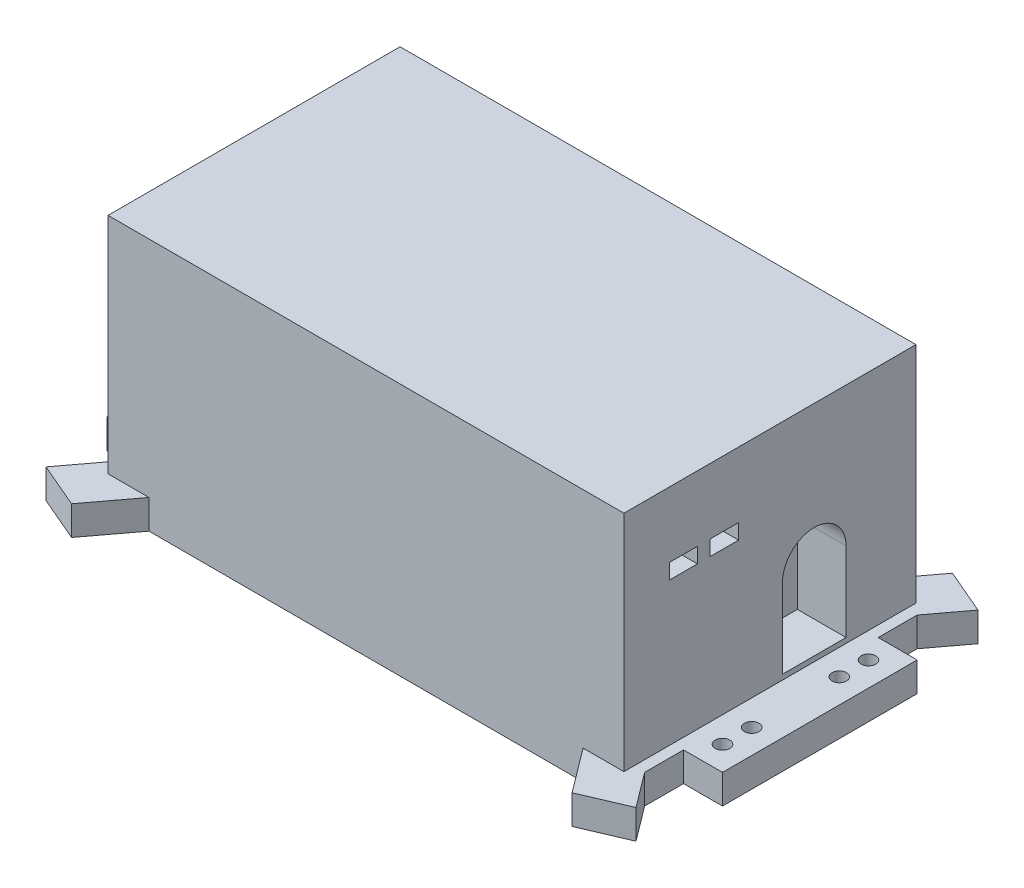
SolidWorks part; units mm, degrees
ref_plane "前视基准面" through (0, 0, 0) normal (0, 0, 1) x (1, 0, 0)
ref_plane "上视基准面" through (0, 0, 0) normal (0, 1, 0) x (1, 0, 0)
ref_plane "右视基准面" through (0, 0, 0) normal (1, 0, 0) x (0, 0, -1)
sketch "草图1" plane through (0, 0, 0) normal (0, 1, 0) x (1, 0, 0)
  line L0 (-65.7171, 0) -> (87.7991, 0) construction
  line L1 (44.6018, -30) -> (-44.6018, -30)
  line L3 (44.6018, 30) -> (-44.6018, 30)
  line L5 (53, -30) -> (-53, 30) construction
  line L6 (53, 30) -> (-53, -30) construction
  line L8 (63.25, -20) -> (63.25, 20)
  line L10 (-63.25, -20) -> (-63.25, 20)
  line L11 (63.25, 20) -> (55.25, 20)
  line L12 (55.25, 20) -> (55.25, 28)
  line L13 (55.25, 28) -> (60.6154, 35.1388)
  line L14 (60.6154, 35.1388) -> (51.4231, 39.0759)
  line L15 (51.4231, 39.0759) -> (44.6018, 30)
  line L16 (63.25, -20) -> (55.25, -20)
  line L17 (55.25, -20) -> (55.25, -28)
  line L18 (55.25, -28) -> (60.6154, -35.1388)
  line L19 (60.6154, -35.1388) -> (51.4231, -39.0759)
  line L20 (51.4231, -39.0759) -> (44.6018, -30)
  line L21 (0, -33.7082) -> (0, 42.5182) construction
  line L22 (-51.4231, -39.0759) -> (-44.6018, -30)
  line L23 (-60.6154, -35.1388) -> (-51.4231, -39.0759)
  line L24 (-55.25, -28) -> (-60.6154, -35.1388)
  line L25 (-55.25, -20) -> (-55.25, -28)
  line L26 (-63.25, -20) -> (-55.25, -20)
  line L27 (-63.25, 20) -> (-55.25, 20)
  line L28 (-55.25, 20) -> (-55.25, 28)
  line L29 (-55.25, 28) -> (-60.6154, 35.1388)
  line L30 (-51.4231, 39.0759) -> (-44.6018, 30)
  line L31 (-60.6154, 35.1388) -> (-51.4231, 39.0759)
  circle A0 centre (58.25, 15) radius 1.5
  circle A1 centre (-58.25, 15) radius 1.5
  circle A2 centre (58.25, 9) radius 1.5
  circle A3 centre (-58.25, 9) radius 1.5
  circle A4 centre (58.25, -9) radius 1.5
  circle A5 centre (58.25, -15) radius 1.5
  circle A6 centre (-58.25, -9) radius 1.5
  circle A7 centre (-58.25, -15) radius 1.5
  point P0 (0, 0)
  point P5 (0, 0)
  dimension "D5" = 3
  dimension "D6" = 3
  dimension "D7" = 3
  dimension "D8" = 3
  dimension "D1" = 60
  dimension "D2" = 106
  dimension "D3" = 40
  dimension "D4" = 126.5
  dimension "D9" = 8
  dimension "D10" = 8
  dimension "D11" = 10
extrude "凸台-拉伸1" add sketch "草图1" along normal blind 6
ref_plane "基准面1" through (0, 6, 0) normal (0, 1, 0) x (1, 0, 0)
sketch "草图2" plane through (0, 6, 0) normal (0, 1, 0) x (1, 0, 0)
  line L1 (53, -30) -> (-53, -30)
  line L2 (53, -30) -> (53, 30)
  line L3 (53, 30) -> (-53, 30)
  line L4 (-53, -30) -> (-53, 30)
  line L5 (53, -30) -> (-53, 30) construction
  line L6 (53, 30) -> (-53, -30) construction
  point P0 (0, 0)
  dimension "D1" = 60
  dimension "D2" = 106
extrude "凸台-拉伸2" add sketch "草图2" along normal blind 46
sketch "草图3" plane through (0, 0, -30) normal (0, 0, -1) x (-1, 0, 0)
  line L1 (-42.197, 39.6989) -> (-14.3671, 39.6989)
  line L2 (-42.197, 39.6989) -> (-42.197, 25.4323)
  line L3 (-42.197, 25.4323) -> (-14.3671, 25.4323)
  line L4 (-14.3671, 39.6989) -> (-14.3671, 25.4323)
  line L5 (-12.2572, 39.6989) -> (15.9746, 39.6989)
  line L6 (-12.2572, 39.6989) -> (-12.2572, 25.4323)
  line L7 (-12.2572, 25.4323) -> (15.9746, 25.4323)
  line L8 (15.9746, 39.6989) -> (15.9746, 25.4323)
  line L9 (-36.2693, 15.9882) -> (-30.3416, 15.9882)
  line L10 (-36.2693, 15.9882) -> (-36.2693, 12.9741)
  line L11 (-36.2693, 12.9741) -> (-30.3416, 12.9741)
  line L12 (-30.3416, 15.9882) -> (-30.3416, 12.9741)
  line L13 (-26.2224, 15.9882) -> (-19.491, 15.9882)
  line L14 (-26.2224, 15.9882) -> (-26.2224, 12.0699)
  line L15 (-26.2224, 12.0699) -> (-19.491, 12.0699)
  line L16 (-19.491, 15.9882) -> (-19.491, 12.0699)
  line L17 (-14.3671, 15.9882) -> (-7.6356, 15.9882)
  line L18 (-14.3671, 15.9882) -> (-14.3671, 12.0699)
  line L19 (-14.3671, 12.0699) -> (-7.6356, 12.0699)
  line L20 (-7.6356, 15.9882) -> (-7.6356, 12.0699)
  circle A0 centre (7.2338, 14.9835) radius 2.9136
extrude "切除-拉伸1" cut sketch "草图3" against normal blind 2
sketch "草图4" plane through (53, 0, 0) normal (1, 0, 0) x (0, 0, -1)
  line L1 (-20.6851, 38.5588) -> (-14.8933, 38.5588)
  line L2 (-20.6851, 38.5588) -> (-20.6851, 35.4265)
  line L3 (-20.6851, 35.4265) -> (-14.8933, 35.4265)
  line L4 (-14.8933, 38.5588) -> (-14.8933, 35.4265)
  line L5 (-12.2929, 38.5588) -> (-6.4419, 38.5588)
  line L6 (-12.2929, 38.5588) -> (-12.2929, 35.4265)
  line L7 (-12.2929, 35.4265) -> (-6.4419, 35.4265)
  line L8 (-6.4419, 38.5588) -> (-6.4419, 35.4265)
  line L9 (2.5667, 23.37) -> (15.6363, 23.37)
  line L10 (2.5667, 23.37) -> (2.5667, 7.0583)
  line L11 (2.5667, 7.0583) -> (15.6363, 7.0583)
  line L12 (15.6363, 23.37) -> (15.6363, 7.0583)
  circle A0 centre (9.1015, 23.37) radius 6.5348
extrude "切除-拉伸2" cut sketch "草图4" against normal blind 10 contours L9 A0 | L9 A0 | A0 L10 L11 L12 | L8 L5 L6 L7 | L4 L1 L2 L3
sketch "草图5" plane through (-53, 0, 0) normal (-1, 0, 0) x (0, 0, 1)
  line L1 (-18.6166, 40.6273) -> (6.9738, 40.6273)
  line L2 (-18.6166, 40.6273) -> (-18.6166, 31.7032)
  line L3 (-18.6166, 31.7032) -> (6.9738, 31.7032)
  line L4 (6.9738, 40.6273) -> (6.9738, 31.7032)
  line L5 (10.5199, 15.1551) -> (24.113, 15.1551)
  line L6 (10.5199, 15.1551) -> (10.5199, 31.7032)
  line L7 (10.5199, 31.7032) -> (24.113, 31.7032)
  line L8 (24.113, 15.1551) -> (24.113, 31.7032)
  circle A0 centre (17.3164, 15.1551) radius 6.7965
extrude "切除-拉伸3" cut sketch "草图5" against normal blind 10 contours A0 L8 L7 L6 | L5 A0 | L5 A0 | L4 L1 L2 L3
